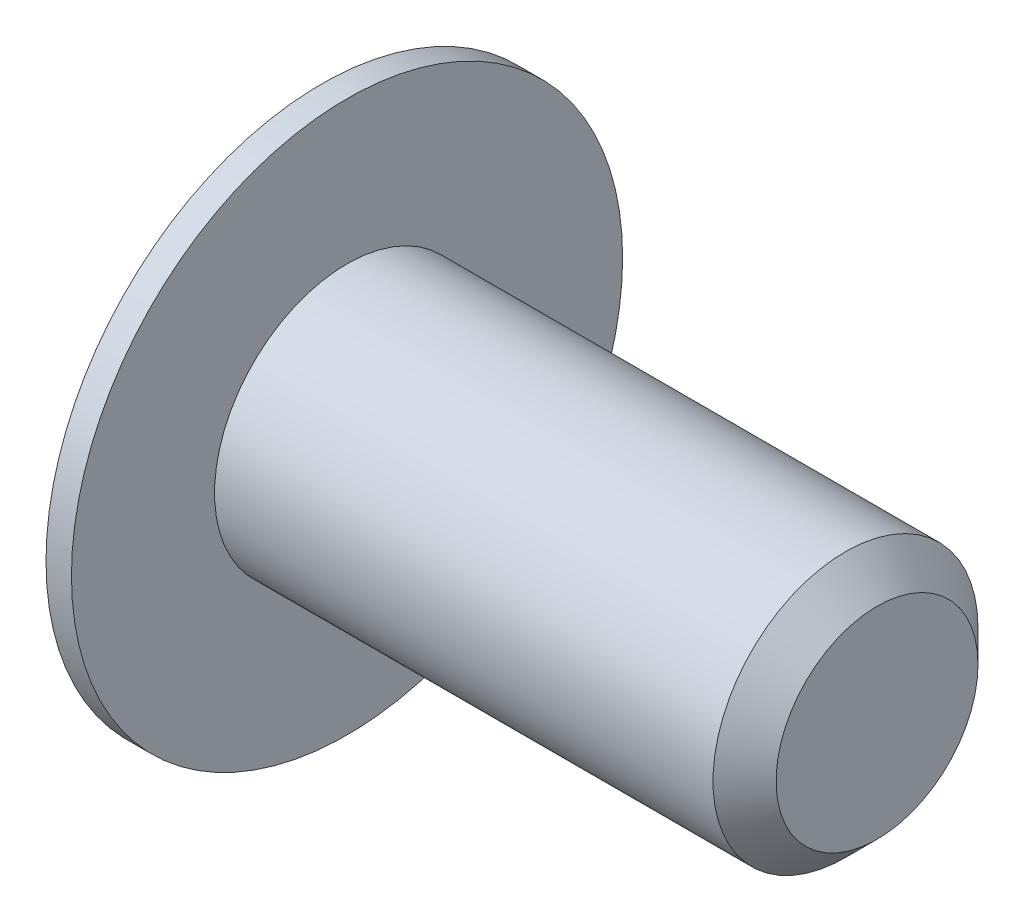
SolidWorks part; units mm, degrees
ref_plane "Front Plane" through (0, 0, 0) normal (0, 0, 1) x (1, 0, 0)
ref_plane "Top Plane" through (0, 0, 0) normal (0, 1, 0) x (1, 0, 0)
ref_plane "Right Plane" through (0, 0, 0) normal (1, 0, 0) x (0, 0, -1)
ref_plane "Plane1" through (0, 0, 0) normal (0, 0, -1) x (-1, 0, 0)
sketch "Sketch1" plane through (0, 0, 0) normal (0, 0, -1) x (-1, 0, 0)
  line L0 (0, 6.604) -> (0, 0)
  line L1 (0, 0) -> (3.048, 0)
  line L2 (3.048, 0) -> (3.048, 2.4384)
  line L3 (0.6096, 5.9436) -> (0.6096, 6.604)
  line L4 (0.6096, 6.604) -> (0, 6.604)
  line L5 (0, 0) -> (3.048, 0) construction
  spline S0 degree 3 poles (0.6096, 5.9436) (1.7565, 5.1007) (2.6566, 3.8068) (3.048, 2.4384) knots 0 0 0 0 1 1 1 1
revolve "Revolve1" add sketch "Sketch1" angle 360 about L5
sketch "Sketch2" plane through (0, 0, 0) normal (1, 0, 0) x (0, 0, -1)
  circle A0 centre (0, 0) radius 3.175
extrude "Boss-Extrude1" add sketch "Sketch2" along normal blind 12.7
sketch "Sketch3" plane through (-3.048, 0, 0) normal (-1, 0, 0) x (0, 0, 1)
  line L0 (0, -2.3464) -> (2.032, -1.1732)
  line L1 (2.032, -1.1732) -> (2.032, 1.1732)
  line L2 (2.032, 1.1732) -> (0, 2.3464)
  line L3 (0, 2.3464) -> (-2.032, 1.1732)
  line L4 (-2.032, 1.1732) -> (-2.032, -1.1732)
  line L5 (-2.032, -1.1732) -> (0, -2.3464)
extrude "Cut-Extrude1" cut sketch "Sketch3" against normal blind 2.286
chamfer "Chamfer1" distance 0.7556 angle 45 1 edges at (12.7, 0, -3.175)
